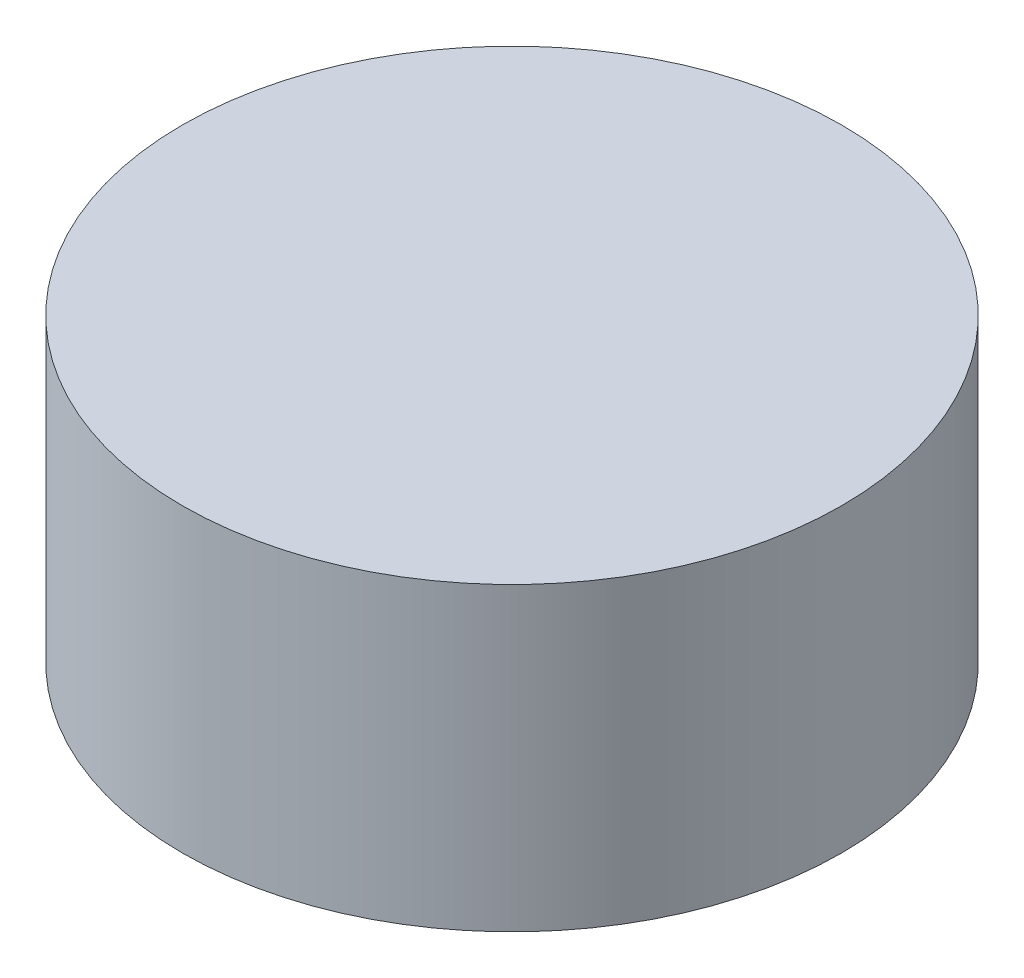
SolidWorks part; units mm, degrees
ref_plane "前视基准面" through (0, 0, 0) normal (0, 0, 1) x (1, 0, 0)
ref_plane "上视基准面" through (0, 0, 0) normal (0, 1, 0) x (1, 0, 0)
ref_plane "右视基准面" through (0, 0, 0) normal (1, 0, 0) x (0, 0, -1)
sketch "草图1" plane through (0, 0, 0) normal (0, 1, 0) x (1, 0, 0)
  circle A0 centre (0, 0) radius 55
extrude "凸台-拉伸1" add sketch "草图1" along normal blind 50
shell "抽壳1" thickness 2
ref_plane "基准面4" through (0, 52, 0) normal (0, 1, 0) x (1, 0, 0)
sketch "草图2" plane through (0, 52, 0) normal (0, 1, 0) x (1, 0, 0)
  arc A0 (0, -30) -> (-52.9389, 21.13) centre (-0.9044, 22.0344) cw
  circle A1 centre (0, 0) radius 57 construction
  arc A2 (0, -30) -> (52.9389, 21.13) centre (0.9044, 22.0344) ccw
  arc A3 (-51.8712, 23.63) -> (0, -27.5) centre (-0.3706, 24.0006) ccw
  arc A4 (51.8712, 23.63) -> (0, -27.5) centre (0.3706, 24.0006) cw
  arc A5 (-52.9389, 21.13) -> (-51.8712, 23.63) centre (0, 0) cw
  arc A6 (51.8712, 23.63) -> (52.9389, 21.13) centre (0, 0) cw
  arc A7 (0, -30) -> (52.9389, 21.13) centre (0.9044, 22.0344) ccw
  arc A8 (51.8712, 23.63) -> (52.9389, 21.13) centre (0, 0) cw
  arc A9 (-51.8712, 23.63) -> (0, -27.5) centre (-0.3706, 24.0006) ccw
  arc A10 (-52.9389, 21.13) -> (-51.8712, 23.63) centre (0, 0) cw
  arc A11 (0, -30) -> (-52.9389, 21.13) centre (-0.9044, 22.0344) cw
  arc A12 (51.8712, 23.63) -> (0, -27.5) centre (0.3706, 24.0006) cw
  point P0 (0, -30)
  point P9 (0, -27.5)
  point P10 (0, -27.5)
  point P11 (-51.8712, 23.63)
  point P12 (0, -30)
  point P13 (51.8712, 23.63)
  dimension "D2" = 2.5
  dimension "D4" = 73.5989
  dimension "D1" = 30
  dimension "D3" = 2.5
